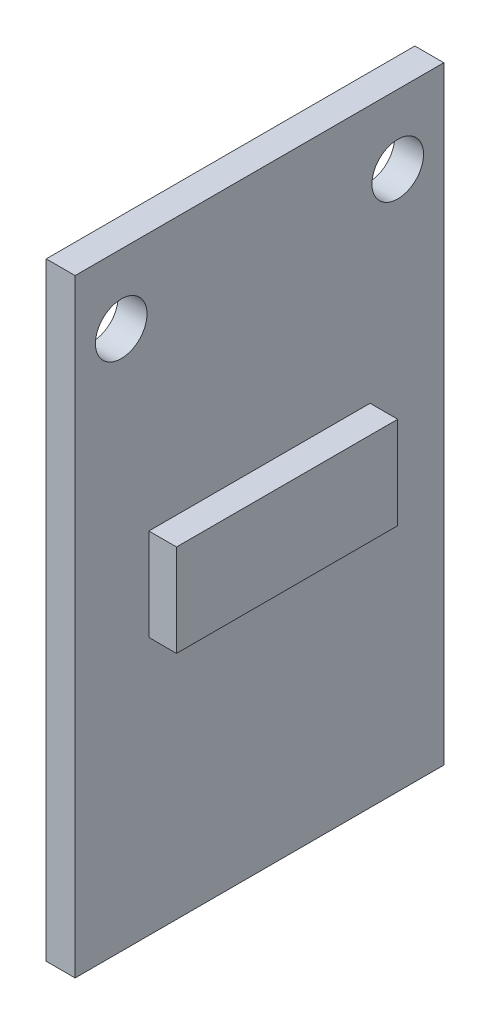
SolidWorks part; units mm, degrees
ref_plane "Front Plane" through (0, 0, 0) normal (1, 0, 0) x (0, 1, 0)
ref_plane "Top Plane" through (0, 0, 0) normal (0, 0, 1) x (0, 1, 0)
ref_plane "Right Plane" through (0, 0, 0) normal (0, 1, 0) x (-1, 0, 0)
sketch "Sketch1" plane through (0, 0, 0) normal (1, 0, 0) x (0, 1, 0)
  line L0 (12.75, 10) -> (12.75, -10) construction
  line L1 (-16.5, -10) -> (16.5, -10)
  line L2 (-16.5, -10) -> (-16.5, 10)
  line L3 (-16.5, 10) -> (16.5, 10)
  line L4 (16.5, -10) -> (16.5, 10)
  line L5 (-16.5, -10) -> (16.5, 10) construction
  line L6 (-16.5, 10) -> (16.5, -10) construction
  circle A0 centre (12.75, 7.5) radius 1.4
  circle A1 centre (12.75, -7.5) radius 1.4
  point P0 (0, 0)
  dimension "D3" = 2.8
  dimension "D4" = 2.8
  dimension "D1" = 33
  dimension "D2" = 20
  dimension "D5" = 3.75
  dimension "D6" = 2.5
  dimension "D7" = 2.5
extrude "Boss-Extrude1" add sketch "Sketch1" along normal blind 1.57
sketch "Sketch2" plane through (1.57, 0, 0) normal (1, 0, 0) x (0, 1, 0)
  line L1 (2.5, -6) -> (-2.5, -6)
  line L2 (2.5, -6) -> (2.5, 6)
  line L3 (2.5, 6) -> (-2.5, 6)
  line L4 (-2.5, -6) -> (-2.5, 6)
  line L5 (2.5, -6) -> (-2.5, 6) construction
  line L6 (2.5, 6) -> (-2.5, -6) construction
  point P0 (0, 0)
  dimension "D1" = 5
  dimension "D2" = 12
extrude "Boss-Extrude2" add sketch "Sketch2" along normal blind 1.5
